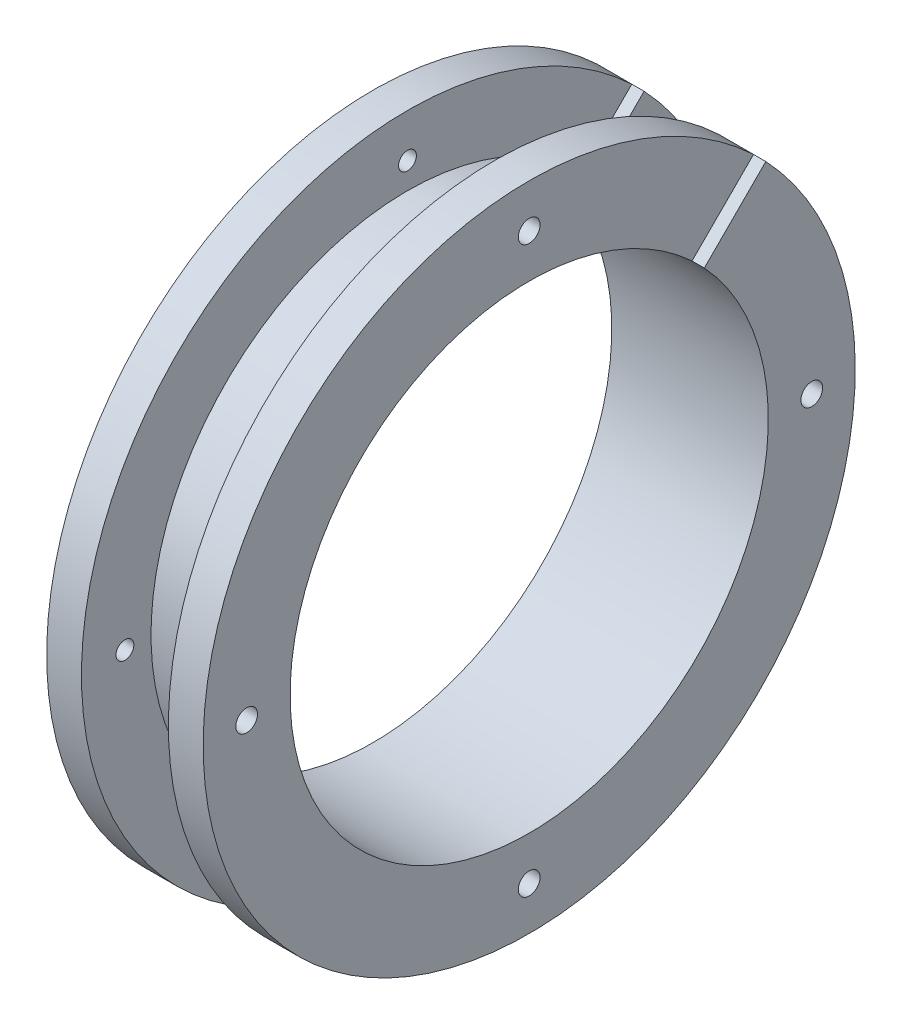
SolidWorks part; units mm, degrees
material "1060 Alloy"
ref_plane "Front Plane" through (0, 0, 0) normal (0, 0, 1) x (1, 0, 0)
ref_plane "Top Plane" through (0, 0, 0) normal (0, 1, 0) x (1, 0, 0)
ref_plane "Right Plane" through (0, 0, 0) normal (1, 0, 0) x (0, 0, -1)
sketch "Sketch1" plane through (0, 0, 0) normal (0, 0, 1) x (1, 0, 0)
  line L0 (0, 0) -> (-116.8977, 0) construction
  line L1 (-18, 27.5) -> (0, 27.5)
  line L2 (0, 27.5) -> (0, 37.5)
  line L3 (0, 37.5) -> (-4, 37.5)
  line L4 (-4, 37.5) -> (-4, 29.5)
  line L5 (-4, 29.5) -> (-14, 29.5)
  line L6 (-14, 29.5) -> (-14, 37.5)
  line L7 (-14, 37.5) -> (-18, 37.5)
  line L8 (-18, 37.5) -> (-18, 27.5)
  dimension "D1" = 37.5
  dimension "D2" = 4
  dimension "D3" = 4
  dimension "D4" = 10
  dimension "D5" = 10
  dimension "D6" = 2
revolve "Revolve1" add sketch "Sketch1" angle 360 about L0
hole_wizard "M2.5x0.45 Tapped Hole2" positions "Sketch5" profile "Sketch4" tap size "M2.5x0.45" standard "Ansi Metric"
sketch "Sketch5" plane through (-18, 0, 0) normal (-1, 0, 0) x (0, 0, 1)
  point P5 (0, -32.5)
  point P8 (-32.5, 0)
  point P14 (32.5, 0)
  point P17 (0, 32.5)
sketch "Sketch4" plane through (-18, -32.5, 0) normal (0, 1, 0) x (0, 0, 1)
  line L0 (0, 0) -> (0, 6.9659)
  line L1 (0, 6.9659) -> (1.025, 6.35)
  line L2 (1.025, 6.35) -> (1.025, 0)
  line L5 (1.025, 0) -> (0, 0)
  line L10 (0, 6.9659) -> (-1.025, 6.35) construction
  line L11 (0, -6.35) -> (0, 107.95) construction
  dimension "Tap Drill Dia." = 2.05
  dimension "Tap Drill Depth" = 6.35
  dimension "Drill Angle" = 118
cosmetic thread "Hole Thread5" parameters "D1"=5, "D2"=2.5
cosmetic thread "Hole Thread6" parameters "D1"=5, "D2"=2.5
cosmetic thread "Hole Thread7" parameters "D1"=5, "D2"=2.5
cosmetic thread "Hole Thread8" parameters "D1"=5, "D2"=2.5
hole_wizard "M3x0.5 Tapped Hole1" positions "Sketch7" profile "Sketch6" tap size "M3x0.5" standard "Ansi Metric"
sketch "Sketch7" plane through (0, 0, 0) normal (1, 0, 0) x (0, 0, -1)
  circle A0 centre (0, 32.5) radius 1.025 construction
  circle A1 centre (-32.5, 0) radius 1.025 construction
  circle A2 centre (0, -32.5) radius 1.025 construction
  point P0 (-32.5, 0)
  point P1 (0, -32.5)
  point P3 (32.5, 0)
  point P6 (0, 32.5)
sketch "Sketch6" plane through (0, 0, 32.5) normal (0, 1, 0) x (0, 0, -1)
  line L0 (0, 0) -> (0, 8.2511)
  line L1 (0, 8.2511) -> (1.25, 7.5)
  line L2 (1.25, 7.5) -> (1.25, 0)
  line L5 (1.25, 0) -> (0, 0)
  line L10 (0, 8.2511) -> (-1.25, 7.5) construction
  line L11 (0, -6.35) -> (0, 107.95) construction
  dimension "Tap Drill Dia." = 2.5
  dimension "Tap Drill Depth" = 7.5
  dimension "Drill Angle" = 118
cosmetic thread "Hole Thread9" parameters "D1"=5, "D2"=3
cosmetic thread "Hole Thread10" parameters "D1"=5, "D2"=3
cosmetic thread "Hole Thread11" parameters "D1"=5, "D2"=3
cosmetic thread "Hole Thread12" parameters "D1"=5, "D2"=3
sketch "Sketch8" plane through (-18, 0, 0) normal (-1, 0, 0) x (0, 0, 1)
  line L0 (0, 32.5) -> (0, 0) construction
  line L1 (0, 0) -> (-32.5, 0) construction
  line L2 (-32.5, 0) -> (0, 32.5) construction
  line L3 (0, 0) -> (-16.25, 16.25) construction
  line L4 (-27.2236, 25.8094) -> (-25.8094, 27.2236)
  line L5 (-25.8094, 27.2236) -> (-18.7255, 20.1397)
  line L6 (-18.7255, 20.1397) -> (-20.1397, 18.7255)
  line L7 (-20.1397, 18.7255) -> (-27.2236, 25.8094)
  circle A1 centre (0, 0) radius 27.5 construction
  circle A2 centre (0, 0) radius 37.5 construction
  dimension "D1" = 2
extrude "Cut-Extrude1" cut sketch "Sketch8" against normal through all
